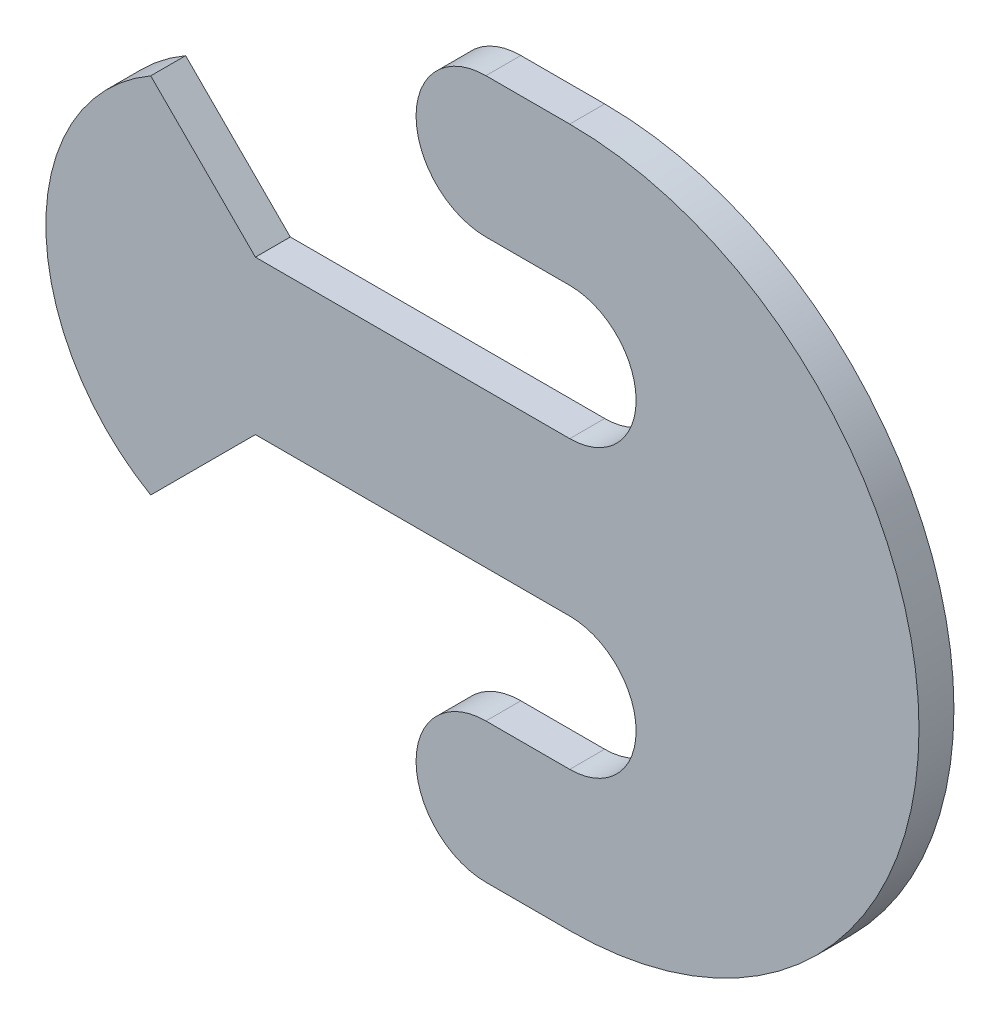
SolidWorks part; units mm, degrees
ref_plane "Front Plane" through (0, 0, 0) normal (0, 0, 1) x (1, 0, 0)
ref_plane "Top Plane" through (0, 0, 0) normal (0, 1, 0) x (1, 0, 0)
ref_plane "Right Plane" through (0, 0, 0) normal (1, 0, 0) x (0, 0, -1)
sketch "Sketch1" plane through (0, 0, 0) normal (0, 0, 1) x (1, 0, 0)
  line L0 (45, 11) -> (45, -39) construction
  line L1 (0, 0) -> (45, 0)
  line L2 (0, 0) -> (0, 22)
  line L3 (0, 22) -> (45, 22)
  line L4 (45, 0) -> (45, 22)
  line L5 (45, 11) -> (45, 41) construction
  line L6 (45, 61) -> (33, 61)
  line L7 (33, 61) -> (33, 51) construction
  line L8 (33, 41) -> (45, 41)
  line L9 (45, 41) -> (45, 22) construction
  line L10 (45, 31.5) -> (90.6043, 31.5) construction
  line L11 (45, -39) -> (33, -39)
  line L12 (33, -39) -> (33, -29) construction
  line L13 (33, -19) -> (45, -19)
  line L14 (45, -19) -> (45, 0) construction
  line L17 (0, 22) -> (-14.9878, 36.9878)
  line L18 (0, 11) -> (-99.2395, 11) construction
  line L19 (0, 0) -> (-14.9878, -14.9878)
  arc A0 (45, -39) -> (45, 61) centre (45, 11) ccw
  arc A1 (33, 61) -> (33, 41) centre (33, 51) ccw
  arc A2 (45, 22) -> (45, 41) centre (45, 31.5) ccw
  arc A3 (33, -19) -> (33, -39) centre (33, -29) ccw
  arc A4 (45, -19) -> (45, 0) centre (45, -9.5) ccw
  arc A5 (-14.9878, 36.9878) -> (-14.9878, -14.9878) centre (0, 11) ccw
extrude "Boss-Extrude1" add sketch "Sketch1" along normal blind 5 contours L17 A5 L19 L2 | L1 L4 L3 L2 | A4 L13 A3 L11 A0 L6 A1 L8 A2 L4
